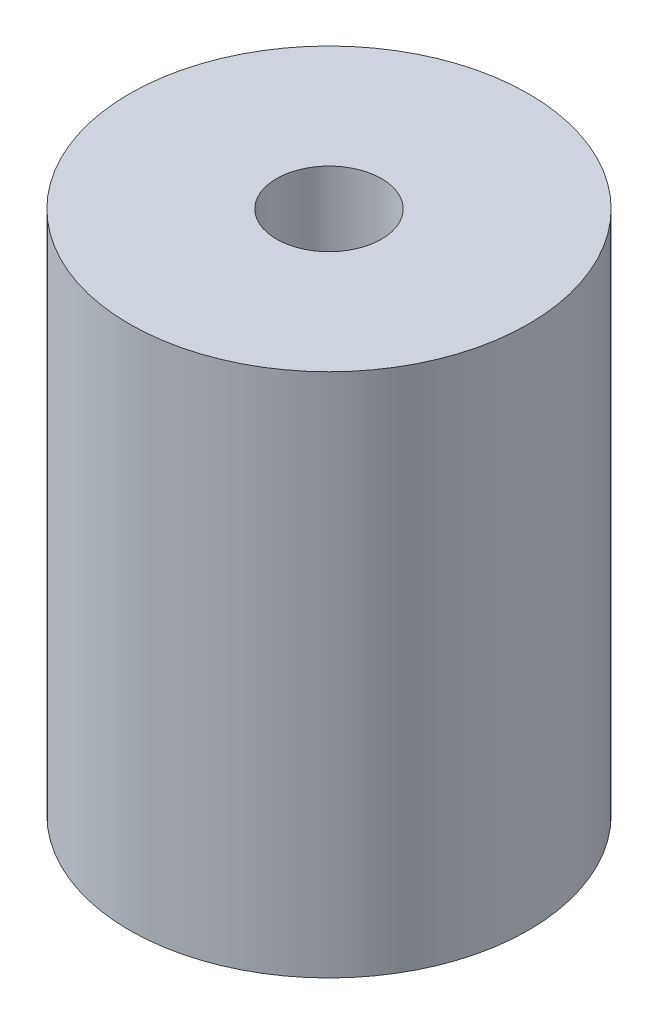
SolidWorks part; units mm, degrees
ref_plane "Front Plane" through (0, 0, 0) normal (0, 0, 1) x (1, 0, 0)
ref_plane "Top Plane" through (0, 0, 0) normal (0, 1, 0) x (1, 0, 0)
ref_plane "Right Plane" through (0, 0, 0) normal (1, 0, 0) x (0, 0, -1)
sketch "Sketch1" plane through (0, 0, 0) normal (0, 0, 1) x (1, 0, 0)
  line L0 (2.5, 0) -> (2.5, 25)
  line L1 (2.5, 25) -> (9.5, 25)
  line L2 (9.5, 25) -> (9.5, 0)
  line L3 (9.5, 0) -> (2.5, 0)
  line L4 (0, 0) -> (0, 25) construction
  point P7 (0, 0)
  point P8 (0, 11.9141)
  point P9 (0, 13.0859)
  dimension "D1" = 5
  dimension "D2" = 19
  dimension "D3" = 25
revolve "Revolve1" add sketch "Sketch1" angle 360 about L4
